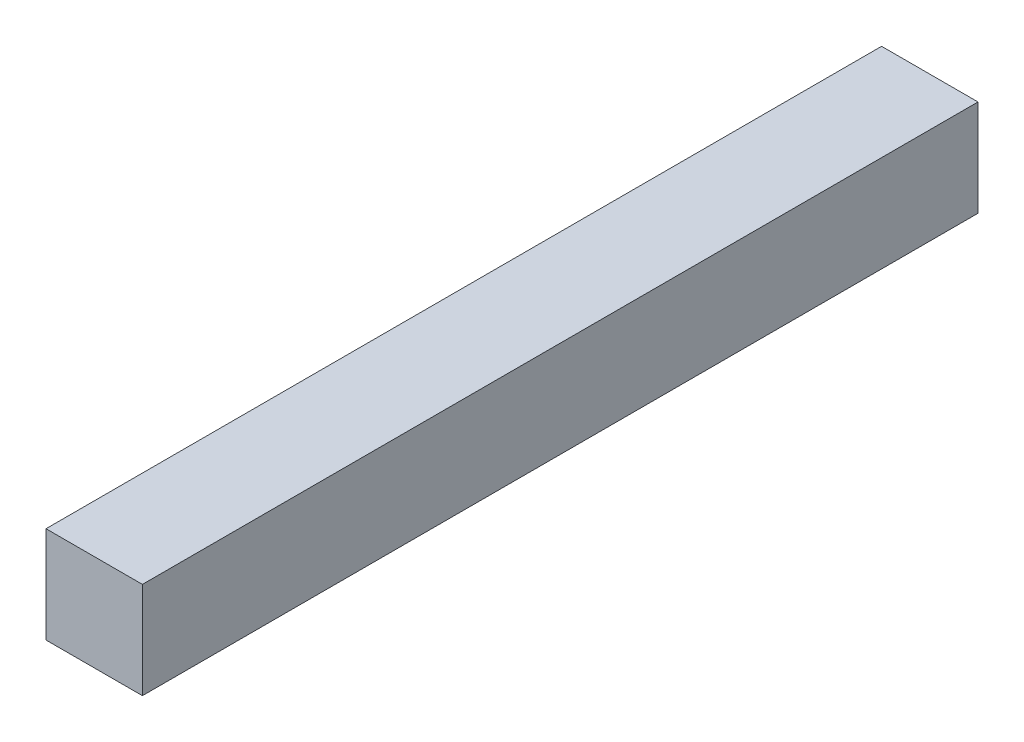
SolidWorks part; units mm, degrees
ref_plane "前基準面" through (0, 0, 0) normal (0, 0, 1) x (1, 0, 0)
ref_plane "上基準面" through (0, 0, 0) normal (0, 1, 0) x (1, 0, 0)
ref_plane "右基準面" through (0, 0, 0) normal (1, 0, 0) x (0, 0, -1)
sketch "草圖1" plane through (0, 0, 0) normal (0, 0, 1) x (1, 0, 0)
  line L1 (15, 15) -> (-15, 15)
  line L2 (15, 15) -> (15, -15)
  line L3 (15, -15) -> (-15, -15)
  line L4 (-15, 15) -> (-15, -15)
  line L5 (0, -15) -> (0, 15) construction
  line L6 (15, 0) -> (-15, 0) construction
  point P0 (0, 0)
  dimension "D1" = 30
  dimension "D2" = 30
extrude "填料-伸長1" add sketch "草圖1" along normal blind 260
